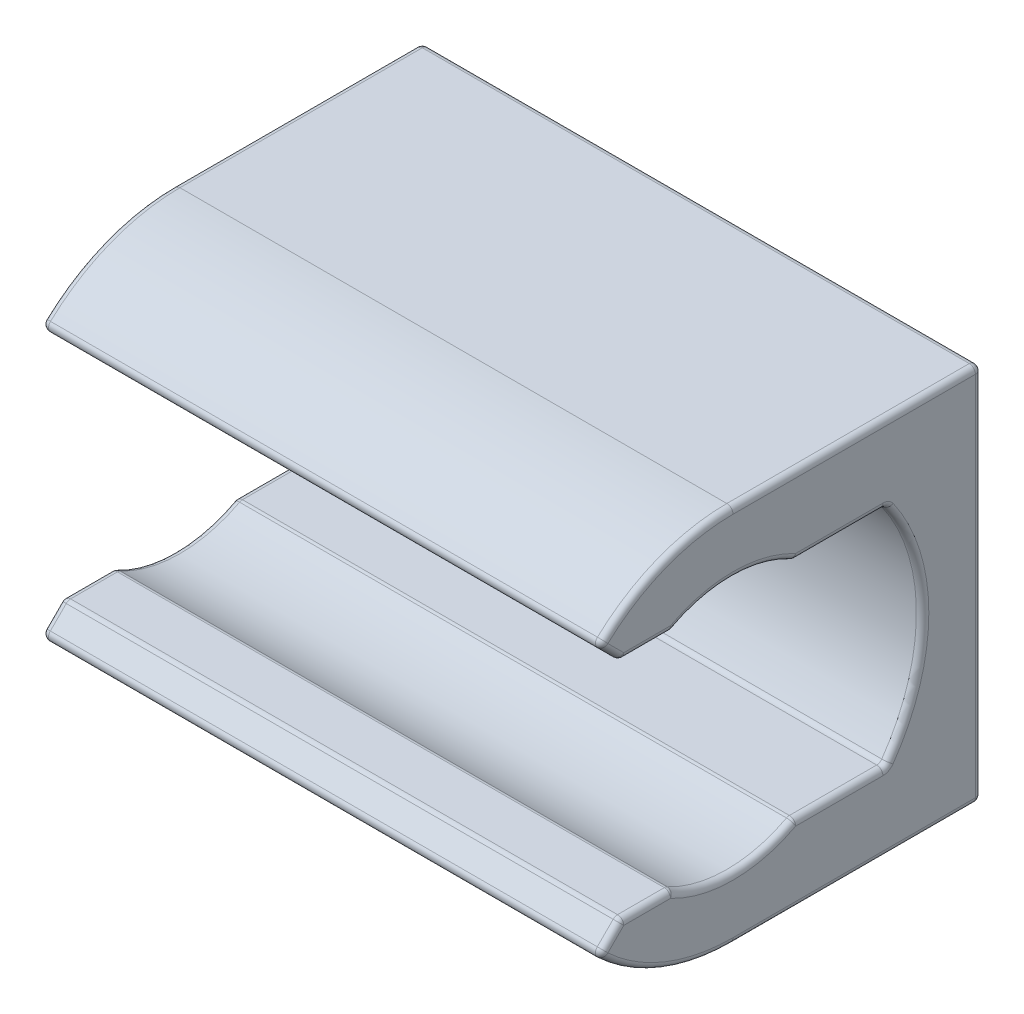
SolidWorks part; units mm, degrees
ref_plane "Front Plane" through (0, 0, 0) normal (0, 0, 1) x (1, 0, 0)
ref_plane "Top Plane" through (0, 0, 0) normal (0, 1, 0) x (1, 0, 0)
ref_plane "Right Plane" through (0, 0, 0) normal (1, 0, 0) x (0, 0, -1)
sketch "Sketch1" plane through (0, 0, 0) normal (1, 0, 0) x (0, 0, -1)
  line L0 (0, 0) -> (-4.3134, 4.3134)
  line L1 (-4.3134, 4.3134) -> (-4.3134, -4.3134)
  line L2 (-4.3134, -4.3134) -> (0, 0)
  line L3 (4.3134, 4.3134) -> (8, 4.3134)
  line L4 (8, 4.3134) -> (8, -4.3134)
  line L5 (8, -4.3134) -> (4.3134, -4.3134)
  line L6 (-8, 3.6) -> (8, 3.6)
  line L7 (-8, -6.1) -> (8, -6.1)
  line L8 (-8, -6.1) -> (-8, 6.1)
  line L9 (-8, 6.1) -> (8, 6.1)
  line L10 (8, -6.1) -> (8, 6.1)
  line L11 (-8, -6.1) -> (8, 6.1) construction
  line L12 (-8, 6.1) -> (8, -6.1) construction
  line L13 (8, -3.6) -> (-8, -3.6)
  circle A0 centre (0, 0) radius 4.1
  circle A1 centre (0, 0) radius 6.1
  dimension "D1" = 8.2
  dimension "D3" = 90
  dimension "D4" = 8
  dimension "D5" = 2.5
  dimension "D6" = 2.5
  dimension "D2" = 2
extrude "Boss-Extrude1" add sketch "Sketch1" along normal blind 18 contours L6 A1 L0 A0 | A1 L3 L10 L9 | A1 L6 L4 L3 | A1 L13 L4 L6 | A1 L7 L10 L5 | A1 L5 L10 L13 | L2 A1 L13 A0
fillet "Fillet1" radius 0.2 40 edges at (9, 4.3134, 4.3134) (9, -4.3134, 4.3134) (9, 6.1, -8) (9, 3.6, 3.6) (9, 3.6, -1.9621) (9, 3.6, 1.9621) (9, 3.6, -4.9244) (9, -3.6, -4.9244) (9, -3.6, 1.9621) (9, -3.6, -1.9621) (9, -3.6, 3.6) (9, -6.1, -8) (0, -6.1, -4) (18, -6.1, -4) (18, -5.6357, 2.3344) (0, -5.6357, 2.3344) (0, -3.9567, 3.9567) (18, -3.9567, 3.9567) (18, -3.6, 2.7811) (0, -3.6, 2.7811) (0, -4.1, 0) (18, -4.1, 0) (18, -3.6, -3.4433) (0, -3.6, -3.4433) (18, 0, -6.1) (0, 0, -6.1) (18, 3.6, -3.4433) (0, 3.6, -3.4433) (0, 4.1, 0) (18, 4.1, 0) (18, 3.6, 2.7811) (0, 3.6, 2.7811) (0, 3.9567, 3.9567) (18, 3.9567, 3.9567) (18, 5.6357, 2.3344) (0, 5.6357, 2.3344) (0, 6.1, -4) (18, 6.1, -4) (0, 0, -8) (18, 0, -8)
